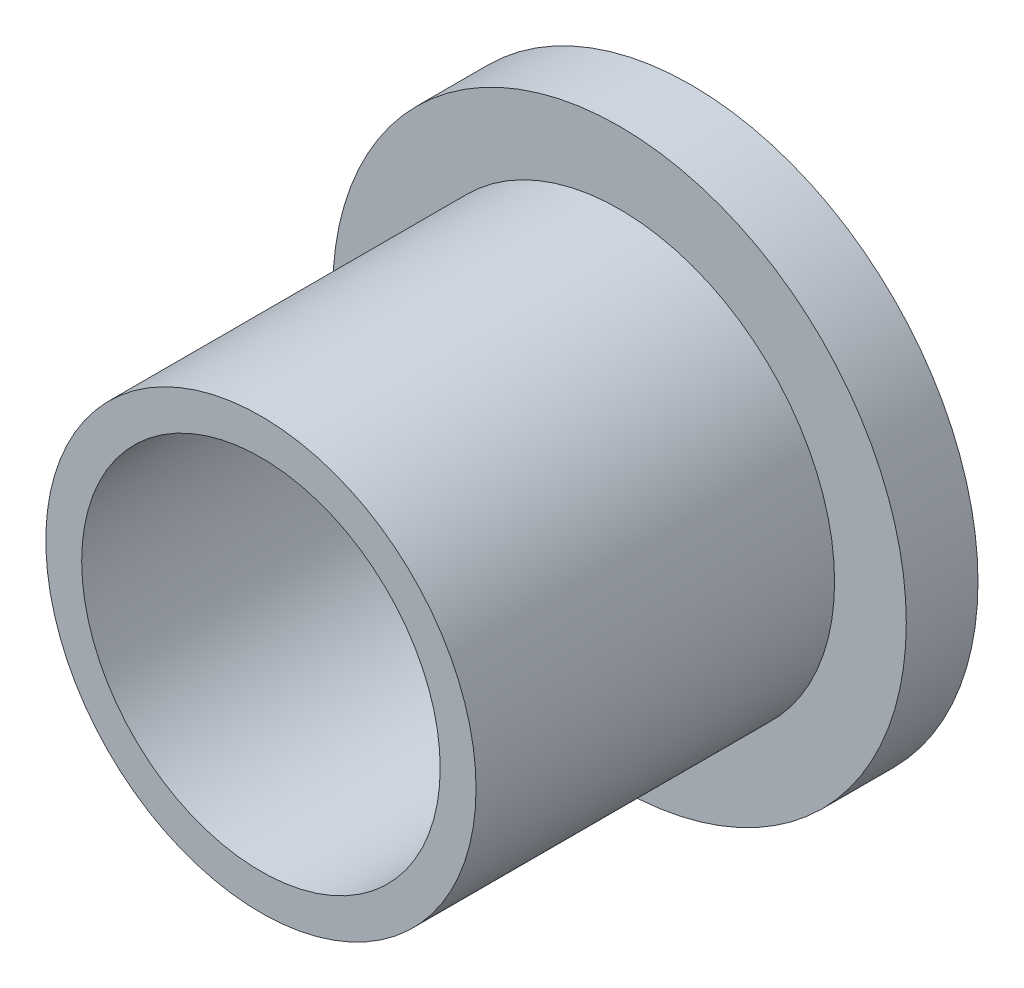
SolidWorks part; units mm, degrees
ref_plane "Alzado" through (0, 0, 0) normal (0, 0, 1) x (1, 0, 0)
ref_plane "Planta" through (0, 0, 0) normal (0, 1, 0) x (1, 0, 0)
ref_plane "Vista lateral" through (0, 0, 0) normal (1, 0, 0) x (0, 0, -1)
sketch "Croquis1" plane through (0, 0, 0) normal (0, 0, 1) x (1, 0, 0)
  circle A0 centre (0, 0) radius 40
  dimension "D1" = 80
extrude "Saliente-Extruir1" add sketch "Croquis1" along normal blind 10
sketch "Croquis2" plane through (0, 0, 10) normal (0, 0, 1) x (1, 0, 0)
  circle A0 centre (0, 0) radius 30
  circle A1 centre (0, 0) radius 25
  dimension "D1" = 60
  dimension "D2" = 50
extrude "Saliente-Extruir2" add sketch "Croquis2" along normal blind 50
